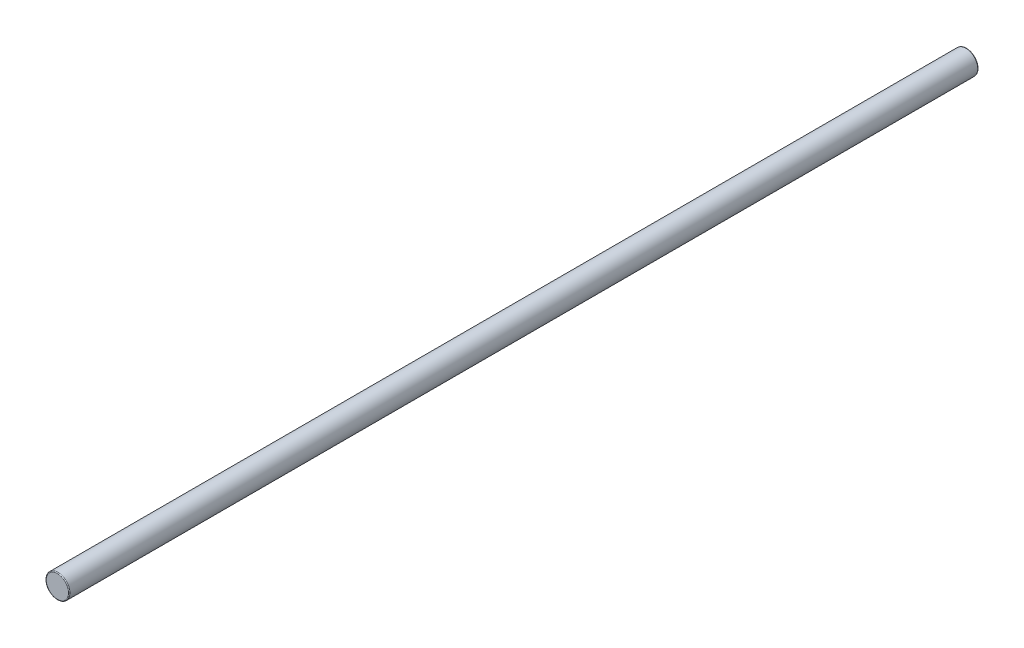
SolidWorks part; units mm, degrees
material "AISI 1020 Steel, Cold Rolled"
ref_plane "Front Plane" through (0, 0, 0) normal (0, 0, 1) x (1, 0, 0)
ref_plane "Top Plane" through (0, 0, 0) normal (0, 1, 0) x (1, 0, 0)
ref_plane "Right Plane" through (0, 0, 0) normal (1, 0, 0) x (0, 0, -1)
sketch "Sketch1" plane through (0, 0, 0) normal (0, 0, 1) x (1, 0, 0)
  circle A0 centre (0, 0) radius 3
  dimension "D1" = 6
extrude "Boss-Extrude1" add sketch "Sketch1" against normal blind 230
fillet "Fillet1" radius 0.2 2 edges at (3, 0, -230) (3, 0, 0)
